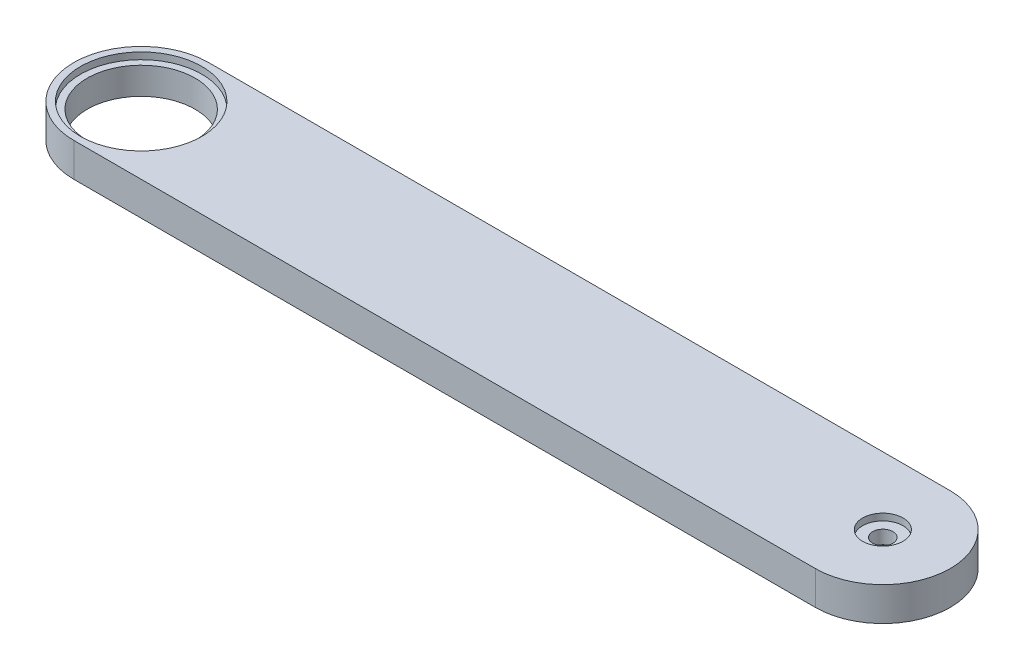
SolidWorks part; units mm, degrees
ref_plane "Front Plane" through (0, 0, 0) normal (0, 0, 1) x (1, 0, 0)
ref_plane "Top Plane" through (0, 0, 0) normal (0, 1, 0) x (1, 0, 0)
ref_plane "Right Plane" through (0, 0, 0) normal (1, 0, 0) x (0, 0, -1)
sketch "Sketch1" plane through (0, 0, 0) normal (0, 1, 0) x (1, 0, 0)
  line L0 (-50, 10) -> (-60, 10)
  line L1 (-50, 10) -> (50, 10)
  line L3 (-60, -10) -> (50, -10)
  arc A1 (50, -10) -> (50, 10) centre (50, 0) ccw
  arc A3 (-60, 10) -> (-60, -10) centre (-60, 0) ccw
  point P0 (0, 0)
  dimension "D1" = 110
  dimension "D2" = 20
extrude "Boss-Extrude1" add sketch "Sketch1" along normal blind 5
sketch "Sketch2" plane through (0, 0, 0) normal (0, -1, 0) x (1, 0, 0)
  line L0 (50, -10) -> (50, 10)
  circle A0 centre (50, 0) radius 4
  dimension "D1" = 8
extrude "Cut-Extrude1" cut sketch "Sketch2" against normal blind 2 contours L0 A0 | L0 A0
sketch "Sketch3" plane through (0, 5, 0) normal (0, 1, 0) x (1, 0, 0)
  line L0 (50, 10) -> (50, -10)
  circle A0 centre (50, 0) radius 3
  dimension "D1" = 6
extrude "Cut-Extrude2" cut sketch "Sketch3" against normal blind 1 contours L0 A0 | L0 A0
sketch "Sketch4" plane through (0, 5, 0) normal (0, 1, 0) x (1, 0, 0)
  line L0 (-60, 10) -> (-60, -10)
  circle A0 centre (-60, 0) radius 8
  dimension "D1" = 16
extrude "Cut-Extrude3" cut sketch "Sketch4" against normal through all contours L0 A0 | L0 A0
sketch "Sketch5" plane through (0, 5, 0) normal (0, 1, 0) x (1, 0, 0)
  circle A0 centre (-60, 0) radius 9
  dimension "D1" = 18
extrude "Cut-Extrude4" cut sketch "Sketch5" against normal blind 1
sketch "Sketch6" plane through (0, 4, 0) normal (0, 1, 0) x (1, 0, 0)
  circle A0 centre (50, 0) radius 1.5
  dimension "D1" = 3
extrude "Cut-Extrude5" cut sketch "Sketch6" against normal through all
